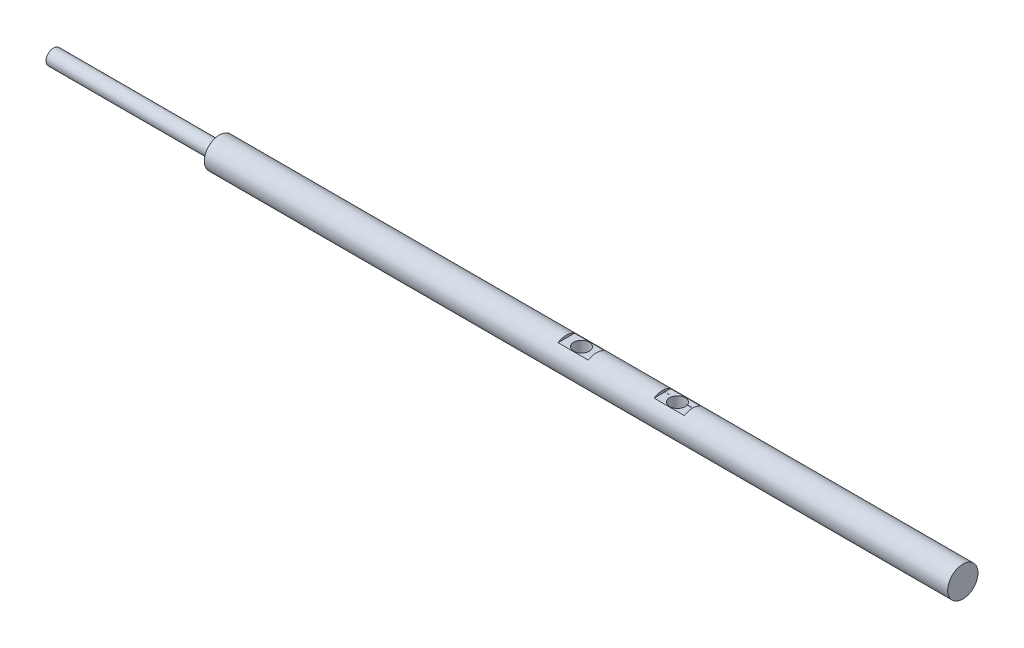
SolidWorks part; units mm, degrees
ref_plane "Front Plane" through (0, 0, 0) normal (0, 0, 1) x (1, 0, 0)
ref_plane "Top Plane" through (0, 0, 0) normal (0, 1, 0) x (1, 0, 0)
ref_plane "Right Plane" through (0, 0, 0) normal (1, 0, 0) x (0, 0, -1)
sketch "Sketch2" plane through (0, 0, 0) normal (1, 0, 0) x (0, 0, -1)
  circle A0 centre (0, 0) radius 3.175
  dimension "D1" = 6.35
extrude "Main Shaft" add sketch "Sketch2" along normal mid plane 190.5
sketch "Sketch3" plane through (0, 0, 0) normal (0, 1, 0) x (1, 0, 0)
  line L0 (-95.25, 0) -> (95.25, 0) construction
  line L1 (95.25, -3.175) -> (95.25, 3.175) construction
  line L2 (25.4, -8.7177) -> (25.4, 8.7177) construction
  circle A0 centre (15.3416, 0) radius 1.632
  circle A1 centre (35.4584, 0) radius 1.6319
  point P6 (0, 0)
  point P10 (25.4, 0)
  dimension "D2" = 3.2639
  dimension "D3" = 20.1168
  dimension "D1" = 120.65
extrude "Pin Holes Cut" cut sketch "Sketch3" against normal through all both and the other way through all
sketch "Sketch5" plane through (0, 0, 0) normal (0, 0, 1) x (1, 0, 0)
  line L0 (16.9735, 3.175) -> (13.7096, 3.175)
  line L1 (33.8265, 3.175) -> (16.9735, 3.175) construction
  line L2 (13.7097, 3.175) -> (-95.25, 3.175) construction
  line L3 (12.1666, 3.175) -> (18.5166, 3.175)
  line L4 (12.1666, 3.175) -> (12.1666, 2.667)
  line L5 (12.1666, 2.667) -> (18.5166, 2.667)
  line L6 (18.5166, 3.175) -> (18.5166, 2.667)
  line L7 (16.9735, -3.175) -> (33.8265, -3.175) construction
  line L8 (33.8265, 3.175) -> (16.9735, 3.175)
  line L9 (16.9735, -3.175) -> (33.8265, -3.175)
  line L10 (25.4, 3.175) -> (25.4, -3.175)
  line L11 (38.6334, 2.6669) -> (32.2834, 2.667)
  line L12 (32.2834, 3.175) -> (32.2834, 2.667)
  line L13 (38.6334, 3.1749) -> (32.2834, 3.175)
  line L14 (38.6334, 3.1749) -> (38.6334, 2.6669)
  spline S0 degree 2 poles (16.9735, 3.175) (15.3416, 2.3362) (13.7096, 3.175) knots 0 0 0 1 1 1 weights 0.001543 0.003175 0.004807 construction
  point P0 (13.7096, 3.175)
  point P10 (15.3416, 3.175)
  point P15 (15.3416, 2.667)
  point P18 (25.4, -3.175)
  point P20 (25.4, 3.175)
  dimension "D1" = 0.508
  dimension "D2" = 6.35
extrude "Flat for drilling Cut" cut sketch "Sketch5" against normal through all both and the other way through all contours L6 L3 L0 L4 L5 | L14 L13 L12 L11
sketch "Sketch6" plane through (-95.25, 0, 0) normal (-1, 0, 0) x (0, 0, 1)
  circle A0 centre (0, 0) radius 1.5875
  circle A1 centre (0, 0) radius 3.175
  circle A2 centre (0, 0) radius 3.175
  dimension "D2" = 3.175
  dimension "D1" = 0
extrude "1/8 Cut" cut sketch "Sketch6" against normal blind 34.7548 and the other way through all
